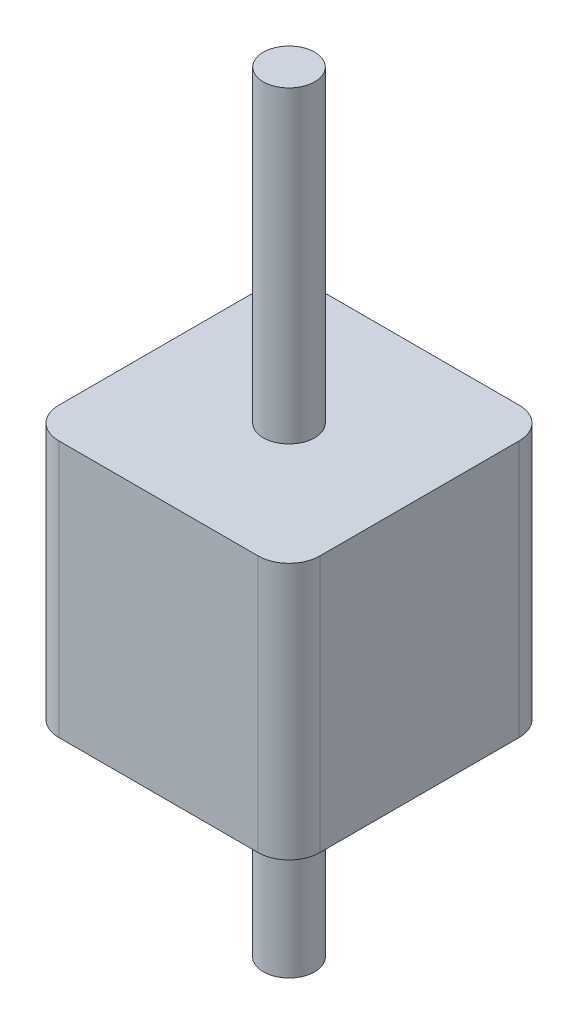
SolidWorks part; units mm, degrees
ref_plane "Front Plane" through (0, 0, 0) normal (0, 0, 1) x (1, 0, 0)
ref_plane "Top Plane" through (0, 0, 0) normal (0, 1, 0) x (1, 0, 0)
ref_plane "Right Plane" through (0, 0, 0) normal (1, 0, 0) x (0, 0, -1)
sketch "Sketch1" plane through (0, 0, 0) normal (0, 1, 0) x (1, 0, 0)
  line L1 (-0.97, -1.27) -> (0.97, -1.27)
  line L2 (-1.27, -0.97) -> (-1.27, 0.97)
  line L3 (-0.97, 1.27) -> (0.97, 1.27)
  line L4 (1.27, -0.97) -> (1.27, 0.97)
  line L5 (-1.27, -1.27) -> (1.27, 1.27) construction
  line L6 (-1.27, 1.27) -> (1.27, -1.27) construction
  arc A0 (0.97, -1.27) -> (1.27, -0.97) centre (0.97, -0.97) ccw
  arc A1 (-0.97, -1.27) -> (-1.27, -0.97) centre (-0.97, -0.97) cw
  arc A2 (0.97, 1.27) -> (1.27, 0.97) centre (0.97, 0.97) cw
  arc A3 (-1.27, 0.97) -> (-0.97, 1.27) centre (-0.97, 0.97) cw
  point P0 (0, 0)
  dimension "D2" = 0.3
  dimension "D1" = 2.54
extrude "Boss-Extrude1" add sketch "Sketch1" along normal blind 2.5
sketch "Sketch2" plane through (0, 2.5, 0) normal (0, 1, 0) x (1, 0, 0)
  circle A0 centre (0, 0) radius 0.25
  dimension "D1" = 0.5
extrude "Boss-Extrude2" add sketch "Sketch2" along normal blind 3
sketch "Sketch3" plane through (0, 0, 0) normal (0, -1, 0) x (1, 0, 0)
  circle A0 centre (0, 0) radius 0.25
  circle A1 centre (0, 0) radius 0.25 construction
extrude "Boss-Extrude3" add sketch "Sketch3" along normal blind 2
